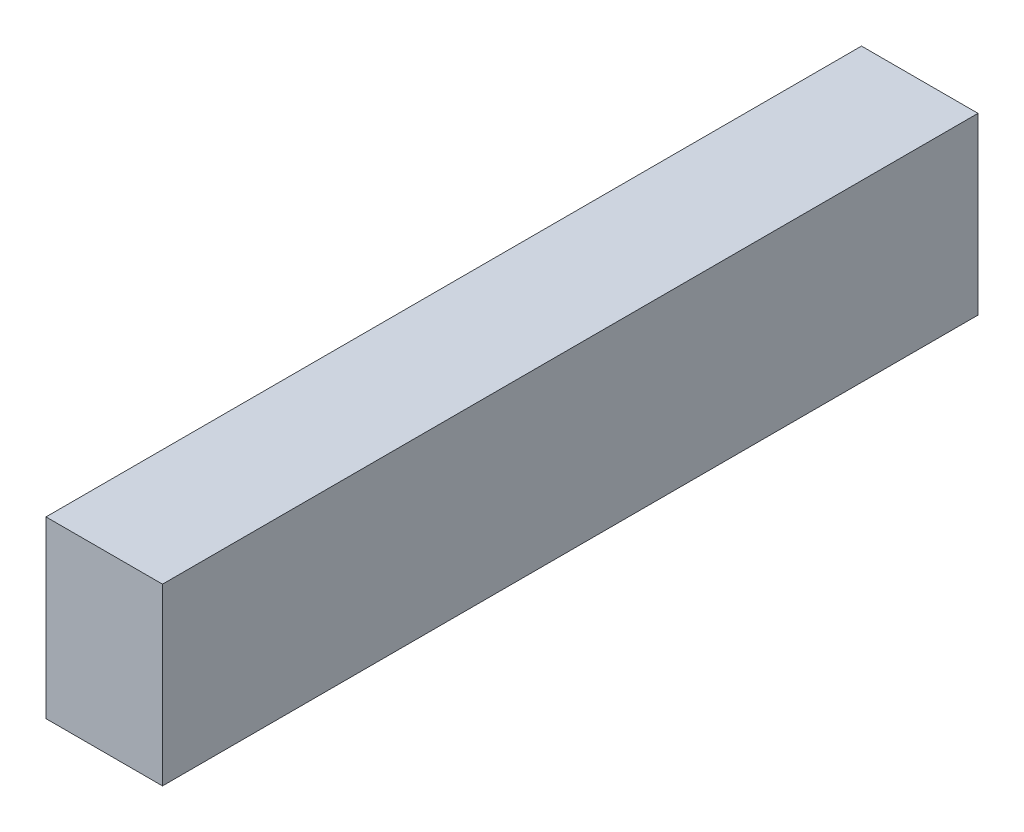
SolidWorks part; units mm, degrees
ref_plane "Front Plane" through (0, 0, 0) normal (0, 0, 1) x (1, 0, 0)
ref_plane "Top Plane" through (0, 0, 0) normal (0, 1, 0) x (1, 0, 0)
ref_plane "Right Plane" through (0, 0, 0) normal (1, 0, 0) x (0, 0, -1)
other "Configuration Table"
sketch "Sketch1" plane through (0, 0, 0) normal (0, 0, 1) x (1, 0, 0)
  line L1 (170, 1254) -> (190, 1254)
  line L2 (170, 1254) -> (170, 1284)
  line L3 (170, 1284) -> (190, 1284)
  line L4 (190, 1254) -> (190, 1284)
extrude "PRESS_uc_pence_parmak_2_1" add sketch "Sketch1" against normal blind 140 from offset 160 separate body
